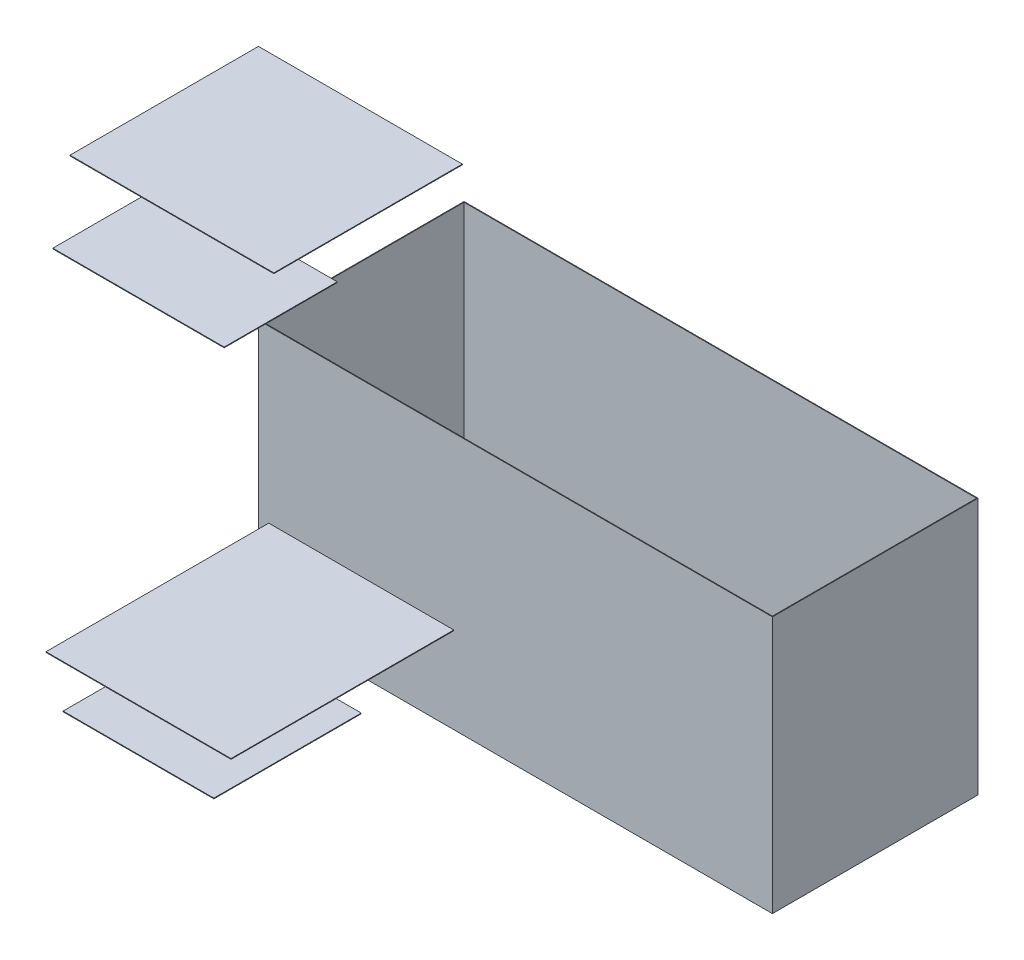
SolidWorks part; units mm, degrees
ref_plane "Спереди" through (0, 0, 0) normal (0, 0, 1) x (1, 0, 0)
ref_plane "Сверху" through (0, 0, 0) normal (0, 1, 0) x (1, 0, 0)
ref_plane "Справа" through (0, 0, 0) normal (1, 0, 0) x (0, 0, -1)
sketch "MASTER_FOOTPRINT" plane through (0, 0, 0) normal (0, 1, 0) x (1, 0, 0)
  line L1 (0, 0) -> (1500, 0)
  line L2 (0, 0) -> (0, 600)
  line L3 (0, 600) -> (1500, 600)
  line L4 (1500, 0) -> (1500, 600)
  dimension "D1" = 1500
  dimension "D2" = 600
extrude "BATH_BASE_PLATE" add sketch "MASTER_FOOTPRINT" along normal blind 750
shell "BATH_SHELL_2MM" thickness 2
sketch "Эскиз1" plane through (0, 0, 0) normal (0, 1, 0) x (1, 0, 0)
  line L1 (80, -220) -> (520, -220)
  line L2 (80, -220) -> (80, -650)
  line L3 (80, -650) -> (520, -650)
  line L4 (520, -220) -> (520, -650)
extrude "INLET_IMPACT_BAFFLE" add sketch "Эскиз1" along normal blind 2 from offset 125 separate body
sketch "Эскиз2" plane through (0, 0, 0) normal (0, 1, 0) x (1, 0, 0)
  line L0 (2, 2) -> (1498, 2) construction
  line L1 (30, 2) -> (570, 2)
  line L2 (30, 2) -> (30, -650)
  line L3 (30, -650) -> (570, -650)
  line L4 (570, 2) -> (570, -650)
  circle A0 centre (49.2857, -125) radius 11
  circle A1 centre (87.8571, -125) radius 11
  circle A2 centre (126.4286, -125) radius 11
  circle A3 centre (165, -125) radius 11
  circle A4 centre (203.5714, -125) radius 11
  circle A5 centre (242.1429, -125) radius 11
  circle A6 centre (280.7143, -125) radius 11
  circle A7 centre (319.2857, -125) radius 11
  circle A8 centre (357.8571, -125) radius 11
  circle A9 centre (396.4286, -125) radius 11
  circle A10 centre (435, -125) radius 11
  circle A11 centre (473.5714, -125) radius 11
  circle A12 centre (512.1429, -125) radius 11
  circle A13 centre (512.1429, -239) radius 7.8571
  circle A14 centre (512.1429, -267.5) radius 7.8571
  circle A15 centre (512.1429, -296) radius 7.8571
  circle A16 centre (512.1429, -324.5) radius 7.8571
  circle A17 centre (512.1429, -353) radius 7.8571
  circle A18 centre (512.1429, -381.5) radius 7.8571
  circle A19 centre (512.1429, -410) radius 7.8571
  circle A20 centre (512.1429, -438.5) radius 7.8571
  circle A21 centre (512.1429, -467) radius 7.8571
  circle A22 centre (512.1429, -495.5) radius 7.8571
  circle A23 centre (512.1429, -524) radius 7.8571
  circle A24 centre (550.7143, -125) radius 19.2857
  circle A25 centre (550.7143, -144.2857) radius 19.2857
  circle A26 centre (550.7143, -210.5) radius 19.2857
  circle A27 centre (550.7143, -229.7857) radius 19.2857
  circle A28 centre (550.7143, -296) radius 19.2857
  circle A29 centre (550.7143, -315.2857) radius 19.2857
  circle A30 centre (550.7143, -381.5) radius 19.2857
  circle A31 centre (550.7143, -400.7857) radius 19.2857
  circle A32 centre (550.7143, -467) radius 19.2857
  circle A33 centre (550.7143, -486.2857) radius 19.2857
sketch "Эскиз3" plane through (0, 0, 0) normal (0, 1, 0) x (1, 0, 0)
  line L0 (30, -650) -> (570, -650) construction
  line L1 (50, -320) -> (550, -320)
  line L2 (50, -320) -> (50, -650)
  line L3 (50, -650) -> (550, -650)
  line L4 (550, -320) -> (550, -650)
extrude "OUTLET_SUBMERGED_BAFFLE" add sketch "Эскиз3" along normal blind 2 from offset 1280 separate body
sketch "Эскиз4" plane through (0, 0, 0) normal (0, 1, 0) x (1, 0, 0)
  line L1 (0, 0) -> (595, 0)
  line L2 (0, 0) -> (0, -550)
  line L3 (0, -550) -> (595, -550)
  line L4 (595, 0) -> (595, -550)
extrude "OVERFLOW_WEIR_Z550" add sketch "Эскиз4" along normal blind 2 from offset 1440 separate body
sketch "Эскиз5" plane through (0, 0, 0) normal (0, 1, 0) x (1, 0, 0)
  line L1 (30, 2) -> (570, 2)
  line L2 (30, 2) -> (30, -650)
  line L3 (30, -650) -> (570, -650)
  line L4 (570, 2) -> (570, -650)
extrude "DISTRIBUTOR_SOLID_PANEL" add sketch "Эскиз5" along normal blind 2 from offset 250 separate body
sketch "Эскиз6" plane through (0, 0, 0) normal (0, 1, 0) x (1, 0, 0)
  circle A0 centre (49.2857, -153.5) radius 11
  circle A1 centre (87.8571, -153.5) radius 11
  circle A2 centre (126.4286, -153.5) radius 11
  circle A3 centre (165, -153.5) radius 11
  circle A4 centre (203.5714, -153.5) radius 11
  circle A5 centre (242.1429, -153.5) radius 11
  circle A6 centre (280.7143, -153.5) radius 11
  circle A7 centre (319.2857, -153.5) radius 11
  circle A8 centre (357.8571, -153.5) radius 11
  circle A9 centre (396.4286, -153.5) radius 11
  circle A10 centre (435, -153.5) radius 11
  circle A11 centre (473.5714, -153.5) radius 11
  circle A12 centre (512.1429, -153.5) radius 20.371
  circle A13 centre (512.1429, -173.871) radius 8.129
  circle A14 centre (512.1429, -210.5) radius 19.2857
  circle A15 centre (550.7143, -191.2143) radius 19.2857
  circle A16 centre (550.7143, -210.5) radius 19.2857 construction
  circle A17 centre (550.7143, -276.7143) radius 19.2857
  circle A18 centre (550.7143, -296) radius 19.2857 construction
  circle A19 centre (550.7143, -362.2143) radius 19.2857
  circle A20 centre (550.7143, -381.5) radius 19.2857 construction
  circle A21 centre (550.7143, -447.7143) radius 19.2857
  circle A22 centre (550.7143, -467) radius 19.2857 construction
  circle A23 centre (550.7143, -524) radius 19.2857
equation "\"AI_Q_Peak\"= 0.006"
equation "\"AI_B_Bath\" = 600"
equation "\"AI_L_Settle\" = 1050"
equation "\"AI_L_Inlet\"= 250"
equation "\"AI_L_Outlet\"= 200"
equation "\"AI_L_Bath\" = 1500"
equation "\"AI_H_Water\"= 550"
equation "\"AI_H_Freeboard\"= 200"
equation "\"AI_H_Bath\"= 750"
equation "\"AI_Shell_Thickness\"= 2"
equation "\"AI_Inlet_DN\"= 100"
equation "\"AI_Weir_Width\"= 600"
equation "\"AI_Inlet_Baffle_Offset\"= 125"
equation "\"AI_Distributor_Open_Area\"= 0.28"
equation "\"AI_Distributor_Hole_Dia\"= 22"
equation "\"AI_Distributor_Blind_Zone\"= 110"
equation "\"AI_Outlet_Baffle_Depth\"= 250"
equation "\"AI_Screw_Diameter\"= 100"
equation "\"AI_Screw_Pitch\"= 100"
equation "\"AI_Screw_Angle\"= 30"
equation "\"AI_Screw_Rpm\"= 15"
equation "\"AI_Screw_Clearance\"= 5"
equation "\"AI_Liner_Thickness\"= 5"
equation "\"AI_Discharge_Height\"= 650"
equation "\"AI_Frame_Height\"= 500"
equation "\"D1@MASTER_FOOTPRINT\" = \"AI_L_Bath\""
equation "\"D2@MASTER_FOOTPRINT\" = \"AI_B_Bath\""
equation "\"D1@BATH_BASE_PLATE\" = \"AI_H_Bath\""
